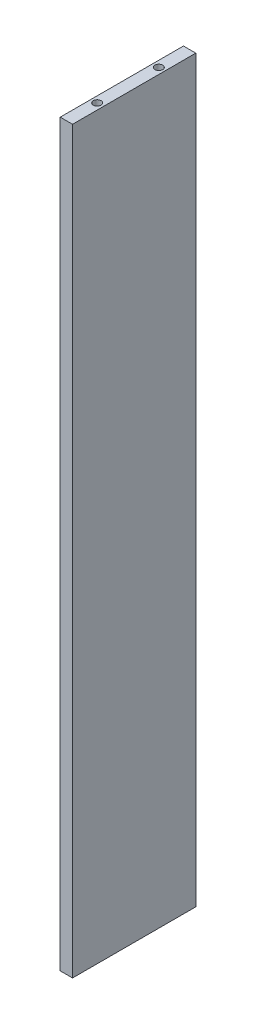
SolidWorks part; units mm, degrees
material "6061 Alloy"
ref_plane "Front Plane" through (0, 0, 0) normal (0, 0, 1) x (1, 0, 0)
ref_plane "Top Plane" through (0, 0, 0) normal (0, 1, 0) x (1, 0, 0)
ref_plane "Right Plane" through (0, 0, 0) normal (1, 0, 0) x (0, 0, -1)
sketch "Sketch1" plane through (0, 0, 0) normal (0, 1, 0) x (1, 0, 0)
  line L0 (0.4399, 58.0587) -> (6.7899, 58.0587)
  line L1 (0.4399, 58.0587) -> (0.4399, -5.4413)
  line L2 (0.4399, -5.4413) -> (6.7899, -5.4413)
  line L3 (6.7899, 58.0587) -> (6.7899, -5.4413)
  dimension "D1" = 63.5
  dimension "D2" = 6.35
extrude "Boss-Extrude1" add sketch "Sketch1" along normal blind 381
sketch "Sketch4" plane through (0, 381, 0) normal (0, 1, 0) x (1, 0, 0)
  line L0 (3.6149, 58.0587) -> (3.6149, 42.1837) construction
  line L1 (6.7899, 58.0587) -> (0.4399, 58.0587) construction
  line L2 (3.6149, 42.1837) -> (3.6149, 10.4337) construction
  line L6 (3.6149, 10.4337) -> (3.6149, -5.4413) construction
  line L7 (0.4399, -5.4413) -> (6.7899, -5.4413) construction
hole_wizard "#10-32 Tapped Hole1" positions "3DSketch1" profile "Sketch5" tap size "#10-32" standard "Ansi Inch"
sketch3d "3DSketch1"
  point P0 (3.6149, 381, -42.1837)
  point P3 (3.6149, 381, -10.4337)
sketch "Sketch5" plane through (3.6149, 381, -42.1837) normal (1, 0, 0) x (0, 0, 1)
  line L0 (0, 0) -> (0, 13.3133)
  line L1 (0, 13.3133) -> (2.0193, 12.1)
  line L2 (2.0193, 12.1) -> (2.0193, 0)
  line L5 (2.0193, 0) -> (0, 0)
  line L10 (0, 13.3133) -> (-2.0193, 12.1) construction
  line L11 (0, -6.35) -> (0, 107.95) construction
  dimension "Tap Drill Dia." = 4.0386
  dimension "Tap Drill Depth" = 12.1
  dimension "Drill Angle" = 118
sketch "Sketch9" plane through (0, 0, 0) normal (0, -1, 0) x (1, 0, 0)
  line L3 (3.6149, 5.4413) -> (3.6149, -10.4337) construction
  line L4 (0.4399, 5.4413) -> (6.7899, 5.4413) construction
  line L5 (3.6149, -10.4337) -> (3.6149, -42.1837) construction
  line L6 (3.6149, -42.1837) -> (3.6149, -58.0587) construction
  line L7 (6.7899, -58.0587) -> (0.4399, -58.0587) construction
hole_wizard "#10-32 Tapped Hole2" positions "3DSketch4" profile "Sketch10" tap size "#10-32" standard "Ansi Inch"
sketch3d "3DSketch4"
  point P0 (3.6149, 0, -10.4337)
  point P3 (3.6149, 0, -42.1837)
sketch "Sketch10" plane through (3.6149, 0, -10.4337) normal (1, 0, 0) x (0, 0, -1)
  line L0 (0, 0) -> (0, 14.9133)
  line L1 (0, 14.9133) -> (2.0193, 13.7)
  line L2 (2.0193, 13.7) -> (2.0193, 0)
  line L5 (2.0193, 0) -> (0, 0)
  line L10 (0, 14.9133) -> (-2.0193, 13.7) construction
  line L11 (0, -6.35) -> (0, 107.95) construction
  dimension "Tap Drill Dia." = 4.0386
  dimension "Tap Drill Depth" = 13.7
  dimension "Drill Angle" = 118
